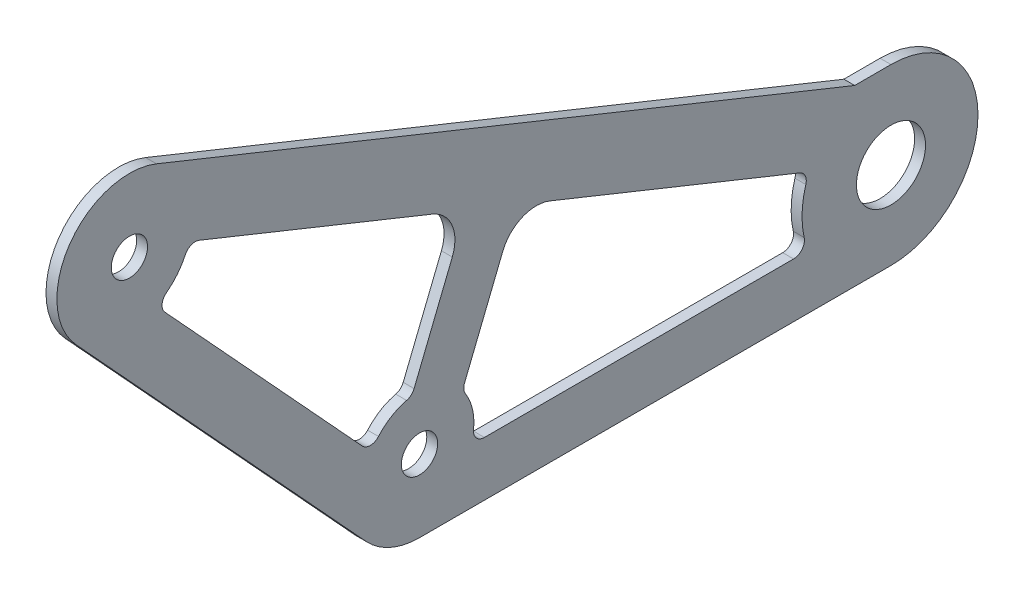
SolidWorks part; units mm, degrees
material "AISI 1020"
ref_plane "Front Plane" through (0, 0, 0) normal (0, 0, 1) x (1, 0, 0)
ref_plane "Top Plane" through (0, 0, 0) normal (0, 1, 0) x (1, 0, 0)
ref_plane "Right Plane" through (0, 0, 0) normal (1, 0, 0) x (0, 0, -1)
sketch "Sketch1" plane through (0, 0, 0) normal (1, 0, 0) x (0, 0, -1)
  line L0 (-65, 0) -> (65, 0)
  line L3 (0, -143.7223) -> (0, 143.7223) construction
  line L4 (-159.722, 93.4625) -> (-79.722, 6.4625)
  line L5 (-137.5273, 125.5515) -> (55, 48)
  line L6 (65, 48) -> (55, 48)
  arc A20 (-137.5273, 125.5515) -> (-159.722, 93.4625) centre (-145, 107) ccw
  arc A22 (-79.722, 6.4625) -> (-65, 0) centre (-65, 20) ccw
  arc A23 (65, 0) -> (65, 48) centre (65, 24) ccw
  point P5 (0, 0)
  point P14 (0, 0)
  dimension "D4" = 127
  dimension "D3" = 24
  dimension "D1" = 10
  dimension "D2" = 130
  dimension "D5" = 20
  dimension "D6" = 20
  dimension "D7" = 254
extrude "Boss-Extrude1" add sketch "Sketch1" along normal blind 3
hole_wizard "3/4 (0.75) Diameter Hole1" positions "Sketch4" profile "Sketch3" hole size "3/4" standard "ANSI Inch" end condition up to next
sketch "Sketch4" plane through (3, 0, 0) normal (1, 0, 0) x (0, 0, -1)
  point P5 (65, 24)
sketch "Sketch3" plane through (3, 24, -65) normal (0, 1, 0) x (0, 0, -1)
  line L0 (0, 0) -> (0, 3)
  line L1 (0, 3) -> (9.525, 3)
  line L2 (9.525, 3) -> (9.525, 0)
  line L5 (9.525, 0) -> (0, 0)
  line L11 (0, -6.35) -> (0, 107.95) construction
  dimension "Thru Hole Dia." = 19.05
  dimension "Thru Hole Depth" = 3
hole_wizard "Ø10.0 (10) Diameter Hole1" positions "Sketch9" profile "Sketch6" hole size "Ø10.0" standard "ANSI Metric" end condition up to next
sketch "Sketch9" plane through (3, 0, 0) normal (1, 0, 0) x (0, 0, -1)
  point P0 (-145, 107)
sketch "Sketch6" plane through (3, 107, 145) normal (0, 1, 0) x (0, 0, -1)
  line L0 (0, 0) -> (0, 3)
  line L1 (0, 3) -> (5, 3)
  line L2 (5, 3) -> (5, 0)
  line L5 (5, 0) -> (0, 0)
  line L11 (0, -6.35) -> (0, 107.95) construction
  dimension "Thru Hole Dia." = 10
  dimension "Thru Hole Depth" = 3
hole_wizard "Ø10.0 (10) Diameter Hole2" positions "Sketch12" profile "Sketch11" hole size "Ø10.0" standard "ANSI Metric" end condition up to next
sketch "Sketch12" plane through (3, 0, 0) normal (1, 0, 0) x (0, 0, -1)
  arc A0 (-79.722, 6.4625) -> (-65, 0) centre (-65, 20) ccw construction
  point P0 (-65, 20)
  point P3 (0, 0)
sketch "Sketch11" plane through (3, 20, 65) normal (0, 1, 0) x (0, 0, -1)
  line L0 (0, 0) -> (0, 3)
  line L1 (0, 3) -> (5, 3)
  line L2 (5, 3) -> (5, 0)
  line L5 (5, 0) -> (0, 0)
  line L11 (0, -6.35) -> (0, 107.95) construction
  dimension "Thru Hole Dia." = 10
  dimension "Thru Hole Depth" = 3
sketch "Sketch8" plane through (3, 0, 0) normal (1, 0, 0) x (0, 0, -1)
  line L0 (38.1369, 15) -> (-47.1115, 15)
  line L1 (39.7682, 34.7301) -> (-29.0364, 62.4451)
  line L2 (-65, 0) -> (65, 0) construction
  line L3 (55, 48) -> (-137.5273, 125.5515) construction
  line L4 (-52.5806, 30.7591) -> (-42.0485, 56.9057)
  line L5 (-135.2109, 88.9674) -> (-80.7888, 29.7834)
  line L6 (-125.7244, 101.3918) -> (-61.5016, 75.5223)
  line L7 (-159.722, 93.4625) -> (-79.722, 6.4625) construction
  line L8 (-66.4942, 36.3636) -> (-55.9621, 62.5102)
  arc A1 (-135.2109, 88.9674) -> (-134.8022, 93.3983) centre (-133.0026, 90.9981) cw
  circle A2 centre (65, 24) radius 24.525
  arc A3 (41.5195, 31.0811) -> (41.0648, 18.654) centre (65, 24) ccw
  circle A4 centre (-145, 107) radius 17
  arc A5 (-134.8022, 93.3983) -> (-129.5685, 99.8677) centre (-145, 107) ccw
  arc A6 (-125.7244, 101.3918) -> (-129.5685, 99.8677) centre (-126.8453, 98.6091) ccw
  arc A7 (38.1369, 15) -> (41.0648, 18.654) centre (38.1369, 18) ccw
  arc A8 (39.7682, 34.7301) -> (41.5195, 31.0811) centre (38.6473, 31.9473) cw
  arc A9 (-29.0364, 62.4451) -> (-42.0485, 56.9057) centre (-32.7727, 53.1693) ccw
  arc A12 (-61.5016, 75.5223) -> (-55.9621, 62.5102) centre (-65.2379, 66.2466) cw
  arc A13 (-50.0929, 18.3333) -> (-52.3315, 28.0318) centre (-65, 20) ccw
  circle A14 centre (-65, 20) radius 15
  arc A15 (-68.5641, 34.5704) -> (-76.3171, 29.845) centre (-65, 20) ccw
  arc A16 (-80.7888, 29.7834) -> (-76.3171, 29.845) centre (-78.5805, 31.814) ccw
  arc A17 (-66.4942, 36.3636) -> (-68.5641, 34.5704) centre (-69.2769, 37.4845) cw
  arc A18 (-52.5806, 30.7591) -> (-52.3315, 28.0318) centre (-49.7978, 29.6382) ccw
  arc A19 (-47.1115, 15) -> (-50.0929, 18.3333) centre (-47.1115, 18) cw
  point P1 (-67.0682, 34.8567)
  point P11 (-78.2534, 27.0247)
  point P18 (-53.1841, 29.2403)
  point P19 (-65, 20)
  point P37 (-50.8579, 15)
  point P48 (-50.8579, 15)
  dimension "D8" = 3
  dimension "D9" = 10
  dimension "D11" = 3
  dimension "D2" = 18
  dimension "D3" = 15
  dimension "D5" = 15
  dimension "D6" = 15
  dimension "D7" = 7.5
  dimension "D1" = 15
  dimension "D4" = 12
  dimension "D10" = 10
extrude "Cut-Extrude1" cut sketch "Sketch8" against normal up to next
equation "\"D7@Sketch8\"=\"D6@Sketch8\"/2"
